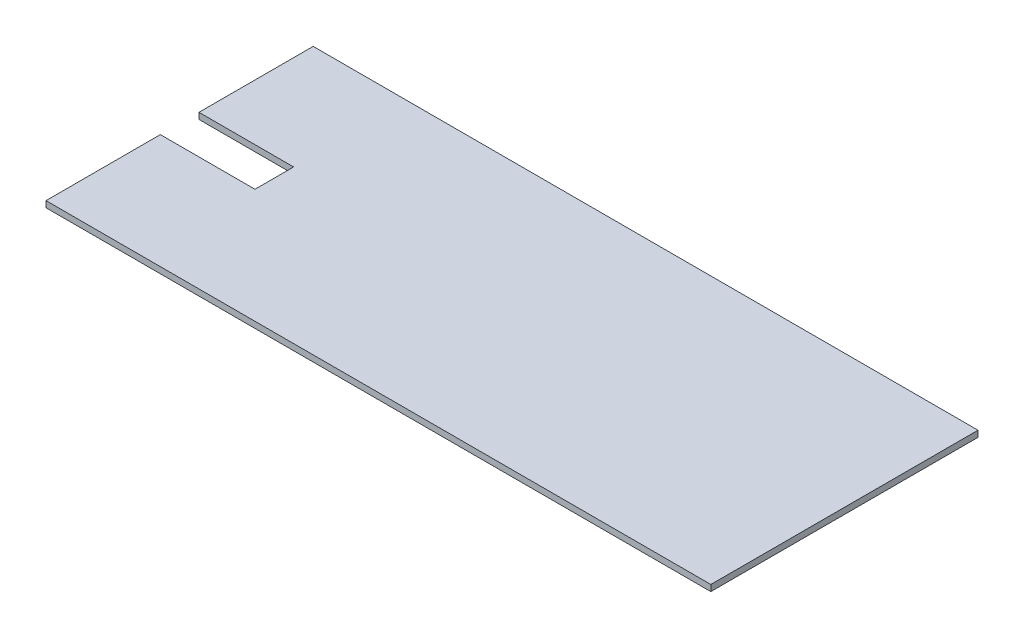
SolidWorks part; units mm, degrees
ref_plane "Спереди" through (0, 0, 0) normal (0, 0, 1) x (1, 0, 0)
ref_plane "Сверху" through (0, 0, 0) normal (0, 1, 0) x (1, 0, 0)
ref_plane "Справа" through (0, 0, 0) normal (1, 0, 0) x (0, 0, -1)
sketch "Эскиз1" plane through (0, 0, 0) normal (0, 1, 0) x (1, 0, 0)
  line L0 (1, -33.7763) -> (31.4666, -33.7763)
  line L1 (1, 2.9847) -> (215, 2.9847)
  line L2 (1, 2.9847) -> (1, -33.7763)
  line L3 (1, -83.0153) -> (215, -83.0153)
  line L4 (215, 2.9847) -> (215, -83.0153)
  line L5 (31.4666, -33.7763) -> (31.4666, -46.2129)
  line L6 (31.4666, -46.2129) -> (1, -46.2129)
  line L7 (1, -46.2129) -> (1, -83.0153)
extrude "Вытянуть1" add sketch "Эскиз1" along normal blind 2
